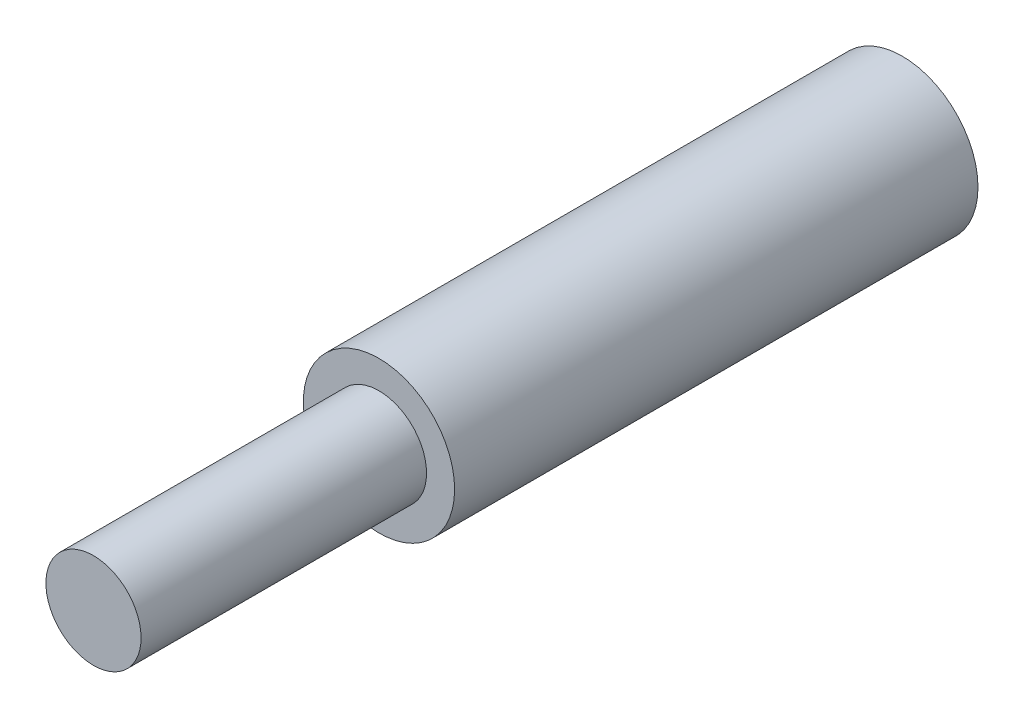
SolidWorks part; units mm, degrees
ref_plane "Front Plane" through (0, 0, 0) normal (0, 0, 1) x (1, 0, 0)
ref_plane "Top Plane" through (0, 0, 0) normal (0, 1, 0) x (1, 0, 0)
ref_plane "Right Plane" through (0, 0, 0) normal (1, 0, 0) x (0, 0, -1)
sketch "Sketch1" plane through (0, 0, 0) normal (0, 0, 1) x (1, 0, 0)
  circle A0 centre (0, 0) radius 1.59
extrude "Boss-Extrude1" add sketch "Sketch1" along normal blind 11
sketch "Sketch2" plane through (0, 0, 11) normal (0, 0, 1) x (1, 0, 0)
  circle A0 centre (0, 0) radius 1
  dimension "D1" = 2
extrude "Boss-Extrude2" add sketch "Sketch2" along normal blind 6
